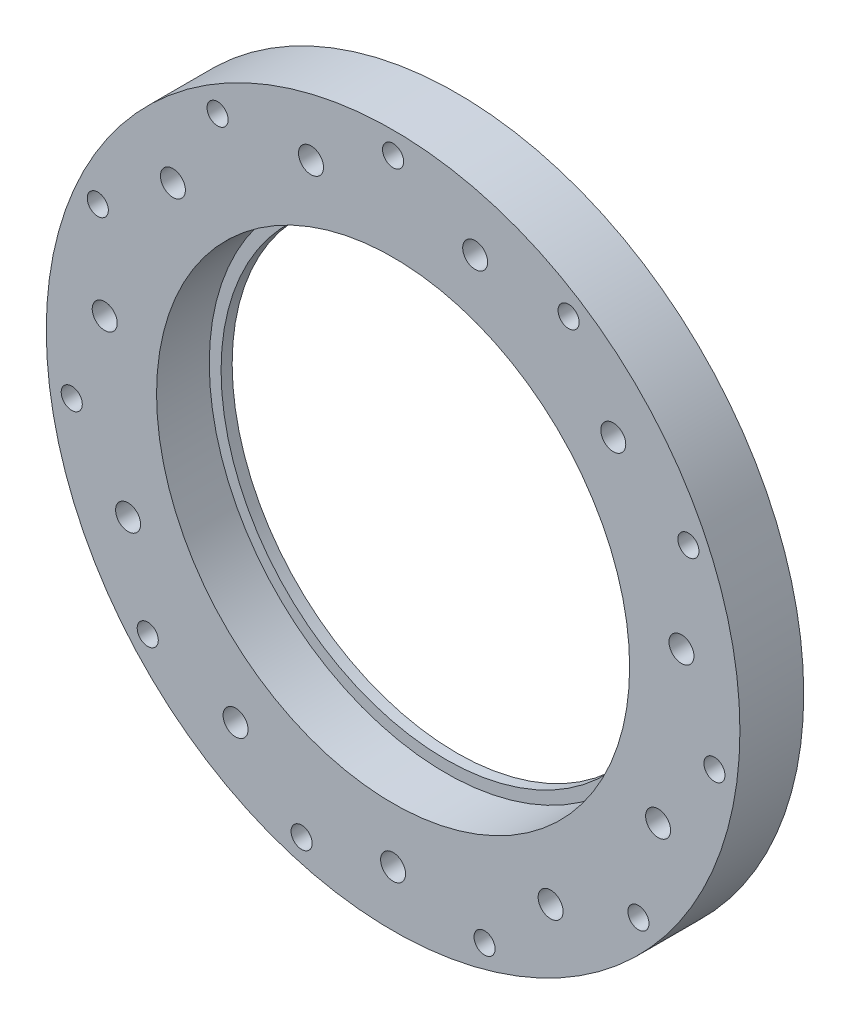
SolidWorks part; units mm, degrees
ref_plane "前视基准面" through (0, 0, 0) normal (0, 0, 1) x (1, 0, 0)
ref_plane "上视基准面" through (0, 0, 0) normal (0, 1, 0) x (1, 0, 0)
ref_plane "右视基准面" through (0, 0, 0) normal (1, 0, 0) x (0, 0, -1)
sketch "草图1" plane through (0, 0, 0) normal (0, 0, 1) x (1, 0, 0)
  line L0 (-28.3836, -44.1658) -> (-47.7557, -21.8093) construction
  line L1 (-38.0697, -32.9875) -> (-64.5237, -55.9101) construction
  circle A0 centre (0, 0) radius 40.5
  circle A1 centre (0, 0) radius 62.5
  circle A2 centre (0, 0) radius 52.5 construction
  circle A3 centre (0, -52.5) radius 2.25
  circle A4 centre (-28.3836, -44.1658) radius 2.25
  circle A5 centre (-47.7557, -21.8093) radius 2.25
  circle A6 centre (-51.9656, 7.4715) radius 2.25
  circle A7 centre (-39.6769, 34.3802) radius 2.25
  circle A8 centre (-14.791, 50.3734) radius 2.25
  circle A9 centre (14.791, 50.3734) radius 2.25
  circle A10 centre (39.6769, 34.3802) radius 2.25
  circle A11 centre (51.9656, 7.4715) radius 2.25
  circle A12 centre (47.7557, -21.8093) radius 2.25
  circle A13 centre (28.3836, -44.1658) radius 2.25
  circle A15 centre (0, 0) radius 58.5 construction
  circle A16 centre (-44.2114, -38.3094) radius 1.9
  circle A17 centre (-57.9046, -8.3254) radius 1.9
  circle A18 centre (-53.2135, 24.3018) radius 1.9
  circle A19 centre (-31.6275, 49.2133) radius 1.9
  circle A20 centre (0, 58.5) radius 1.9
  circle A21 centre (31.6275, 49.2133) radius 1.9
  circle A22 centre (53.2135, 24.3018) radius 1.9
  circle A23 centre (57.9046, -8.3254) radius 1.9
  circle A24 centre (44.2114, -38.3094) radius 1.9
  circle A25 centre (16.4814, -56.1303) radius 1.9
  circle A26 centre (-16.4814, -56.1303) radius 1.9
  dimension "D1" = 81
  dimension "D2" = 125
  dimension "D3" = 105
  dimension "D4" = 4.5
  dimension "D6" = 117
  dimension "D7" = 3.8
  dimension "D5" = 11
  dimension "D8" = 11
extrude "凸台-拉伸1" add sketch "草图1" along normal blind 11.5 contours A0
sketch "草图2" plane through (0, 0, 11.5) normal (0, 0, 1) x (1, 0, 0)
  circle A0 centre (0, 0) radius 42.625
  dimension "D1" = 85.25
extrude "切除-拉伸1" cut sketch "草图2" against normal blind 9.5
